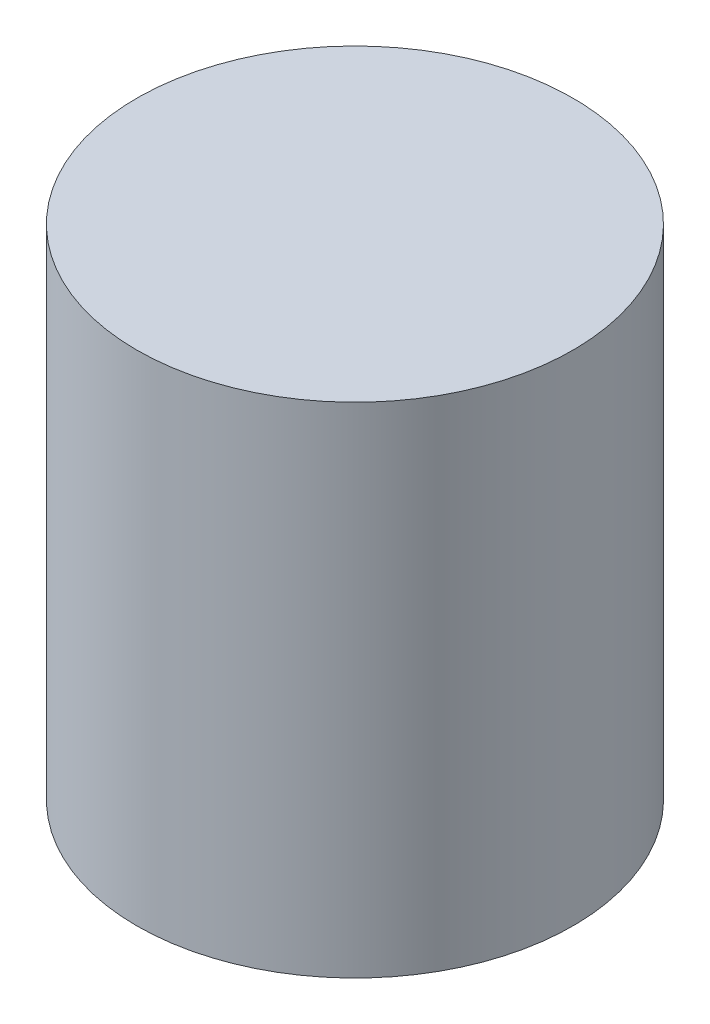
SolidWorks part; units mm, degrees
ref_plane "Front Plane" through (0, 0, 0) normal (0, 0, 1) x (1, 0, 0)
ref_plane "Top Plane" through (0, 0, 0) normal (0, 1, 0) x (1, 0, 0)
ref_plane "Right Plane" through (0, 0, 0) normal (1, 0, 0) x (0, 0, -1)
sketch "Sketch1" plane through (0, 0, 0) normal (0, 1, 0) x (1, 0, 0)
  circle A0 centre (-2.4479, -0.958) radius 1.75
  dimension "D1" = 3.5
extrude "Boss-Extrude1" add sketch "Sketch1" along normal blind 4
